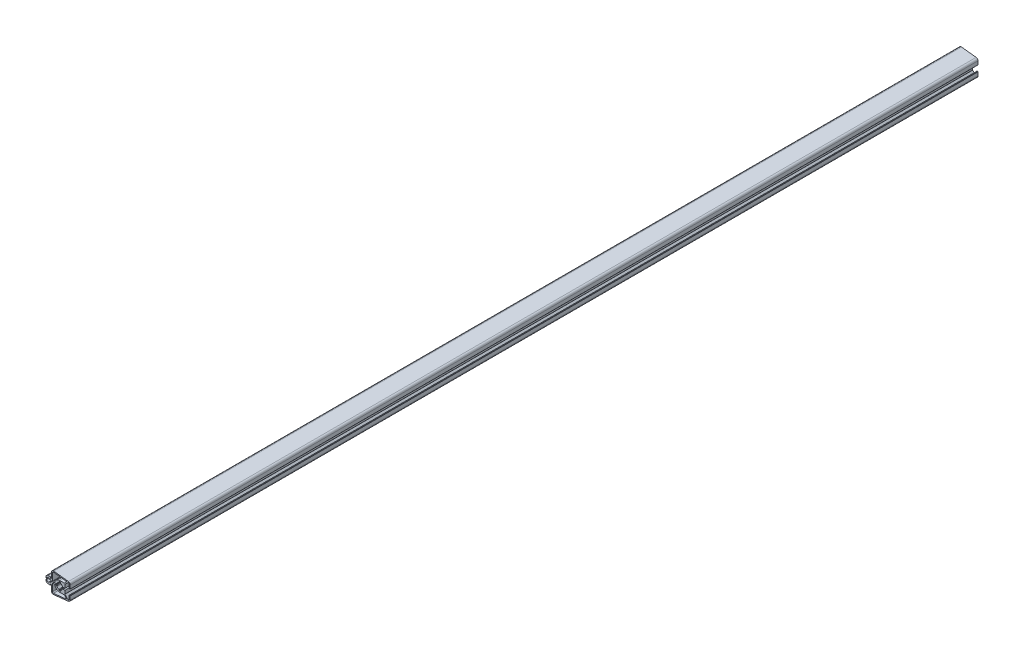
SolidWorks part; units mm, degrees
material "6061 Alloy"
ref_plane "Front Plane" through (0, 0, 0) normal (0, 0, 1) x (1, 0, 0)
ref_plane "Top Plane" through (0, 0, 0) normal (0, 1, 0) x (1, 0, 0)
ref_plane "Right Plane" through (0, 0, 0) normal (1, 0, 0) x (0, 0, -1)
sketch "Sketch1" plane through (0, 0, 0) normal (0, 0, 1) x (1, 0, 0)
  line L0 (27, 23.6023) -> (27, -23.6023) construction
  line L1 (16.5, -1.25) -> (16.5, -11.6482)
  line L2 (21.49, 1.2) -> (22.3417, 1.2)
  line L3 (13.5, 1.5) -> (12.4976, 1.5)
  line L4 (13.5, -1.5) -> (12.4976, -1.5)
  line L5 (0, 23.6023) -> (0, -23.6023) construction
  line L6 (-42, 0) -> (42, 0) construction
  line L7 (7.3, -42) -> (7.3, -0.75) construction
  line L9 (17, 0.75) -> (19.091, 0.75)
  line L10 (18.3313, 14.6299) -> (39.3313, 12.2965) construction
  line L11 (42, 4.3) -> (42, 9.3149) construction
  line L12 (40.5, 4.3) -> (40.5, 9.3149) construction
  line L13 (17, -0.75) -> (19.091, -0.75)
  line L14 (15, 11.6482) -> (15, 3.873)
  line L15 (16.5, 11.6482) -> (16.5, 1.25)
  line L16 (36.8838, -10.7323) -> (33.5101, -7.3586)
  line L17 (39.0532, -10.7804) -> (34.3586, -6.0858)
  line L18 (39.135, -10.8091) -> (39.1656, -10.8057)
  line L19 (28.2, -5.51) -> (28.2, -4.6583)
  line L20 (40.5, -4.3) -> (40.5, -9.3149)
  line L21 (42, -4.3) -> (42, -9.3149)
  line L22 (41.8, -4.1) -> (40.7, -4.1)
  line L23 (18.1656, -13.139) -> (36.7644, -11.0725)
  line L24 (18.3313, -14.6299) -> (39.3313, -12.2965)
  line L26 (16.5, -4.1) -> (10.4, 0) construction
  line L27 (7.3, -0.95) -> (7.3, -2.1377)
  line L28 (15, -11.6482) -> (15, -3.873)
  line L29 (13.5, 4.1495) -> (13.5, 5.04)
  line L30 (27, -7.3) -> (33.3686, -7.3)
  line L31 (34.3, -5.9444) -> (34.3, -1.2)
  line L32 (10.4, 5.14) -> (13.4, 5.14)
  line L33 (7.3, -4.1) -> (42, -4.1) construction
  line L34 (13.5, 4.1) -> (7.3, -4.1) construction
  line L35 (10.4, -5.14) -> (13.4, -5.14)
  line L36 (13.5, -4.1495) -> (13.5, -5.04)
  line L38 (7.3, 0) -> (7.3, 42) construction
  line L39 (7.5, 0.75) -> (7.8726, 0.75)
  line L41 (7.5, -0.75) -> (7.8726, -0.75)
  line L42 (0, 0) -> (-24.914, -24.914) construction
  line L44 (7.3, 2.1377) -> (7.3, 0.95)
  line L45 (14.0524, 0.75) -> (5.7297, 0.75) construction
  line L47 (5.7297, -0.75) -> (14.0524, -0.75) construction
  line L48 (12, 15) -> (42, 15) construction
  line L49 (-45, -45) -> (45, -45) construction
  line L50 (-45, -45) -> (-45, 45) construction
  line L51 (-45, 45) -> (45, 45) construction
  line L52 (45, -45) -> (45, 45) construction
  line L53 (-45, -45) -> (45, 45) construction
  line L54 (-45, 45) -> (45, -45) construction
  line L55 (-42, -42) -> (42, -42) construction
  line L56 (-42, -42) -> (-42, 42) construction
  line L57 (-42, 42) -> (42, 42) construction
  line L58 (42, -42) -> (42, 42) construction
  line L59 (-42, -42) -> (42, 42) construction
  line L60 (-42, 42) -> (42, -42) construction
  line L62 (41.8, 4.1) -> (40.7, 4.1)
  line L63 (42, 4.3) -> (42, 9.3149)
  line L65 (15, 0) -> (15, 42) construction
  line L66 (39.0532, 10.7804) -> (34.3586, 6.0858)
  line L67 (27, 7.3) -> (33.3686, 7.3)
  line L68 (34.3, 5.9444) -> (34.3, 1.2)
  line L69 (18.3313, 14.6299) -> (39.3313, 12.2965)
  line L72 (19.7, 7.3) -> (34.3, -7.3) construction
  line L74 (36.8838, 10.7323) -> (33.5101, 7.3586)
  line L75 (42, 4.3) -> (42, 9.813) construction
  line L76 (18.1656, 13.139) -> (36.7644, 11.0725)
  line L77 (40.5, 4.3) -> (40.5, 9.3149)
  line L78 (38.7929, 10.5201) -> (34.5929, 6.3201) construction
  line L79 (39.135, 10.8091) -> (39.1656, 10.8057)
  line L80 (7.3, 4.1) -> (42, 4.1) construction
  line L81 (40.5, 4.3) -> (40.5, 9.813) construction
  line L82 (18.1656, 13.139) -> (39.1656, 10.8057) construction
  line L83 (37.7322, 11.5808) -> (33.5322, 7.3808) construction
  line L86 (25.8, -5.51) -> (25.8, -4.6583)
  line L88 (16.5, 11.6482) -> (16.5, 0) construction
  line L89 (21.49, -1.2) -> (22.3417, -1.2)
  line L90 (15, 11.6482) -> (15, 0) construction
  line L91 (34.3, -1.2) -> (31.6583, -1.2)
  line L92 (34.3, 1.2) -> (31.6583, 1.2)
  line L93 (25.8, 5.51) -> (25.8, 4.6583)
  line L94 (28.2, 5.51) -> (28.2, 4.6583)
  arc A0 (27, 7.3) -> (19.8279, 1.3602) centre (27, 0) ccw
  arc A1 (19.8279, -1.3602) -> (27, -7.3) centre (27, 0) ccw
  arc A2 (15, 11.6482) -> (18.3313, 14.6299) centre (18, 11.6482) cw
  arc A3 (33.5101, 7.3586) -> (33.3686, 7.3) centre (33.3686, 7.5) cw
  arc A4 (34.3586, 6.0858) -> (34.3, 5.9444) centre (34.5, 5.9444) ccw
  circle A5 centre (10.4, 0) radius 5.14 construction
  arc A6 (14.1365, 3.5296) -> (13.5389, 4.0703) centre (10.4, 0) ccw
  arc A7 (42, 4.3) -> (41.8, 4.1) centre (41.8, 4.3) cw
  arc A8 (40.7, 4.1) -> (40.5, 4.3) centre (40.7, 4.3) cw
  arc A9 (15, 3.873) -> (14.1365, 3.5296) centre (14.5, 3.873) cw
  arc A10 (25.3396, -3.9665) -> (25.8, -4.6583) centre (25.05, -4.6583) cw
  arc A11 (21.2932, 1.0357) -> (21.2932, -1.0357) centre (27, 0) ccw
  arc A12 (10.4, 5.14) -> (10.1598, 5.1344) centre (10.4, 0) ccw
  arc A13 (34.3586, -6.0858) -> (34.3, -5.9444) centre (34.5, -5.9444) cw
  arc A14 (28.2, 5.51) -> (28.0357, 5.7068) centre (28, 5.51) ccw
  arc A15 (33.5101, -7.3586) -> (33.3686, -7.3) centre (33.3686, -7.5) ccw
  arc A16 (39.0532, -10.7804) -> (39.135, -10.8091) centre (39.1239, -10.7097) ccw
  arc A17 (39.1656, -10.8057) -> (40.5, -9.3149) centre (39, -9.3149) ccw
  arc A18 (39.3313, -12.2965) -> (42, -9.3149) centre (39, -9.3149) ccw
  arc A19 (40.7, -4.1) -> (40.5, -4.3) centre (40.7, -4.3) ccw
  arc A20 (42, -4.3) -> (41.8, -4.1) centre (41.8, -4.3) ccw
  arc A21 (18.1656, -13.139) -> (16.5, -11.6482) centre (18, -11.6482) cw
  arc A22 (13.4, 5.14) -> (13.5, 5.04) centre (13.4, 5.04) cw
  arc A23 (13.5, 4.1495) -> (13.5389, 4.0703) centre (13.6, 4.1495) ccw
  arc A24 (10.1598, 5.1344) -> (7.3, 2.1377) centre (10.3, 2.1377) ccw
  arc A25 (17, 0.75) -> (16.5, 1.25) centre (17, 1.25) cw
  arc A26 (15, -11.6482) -> (18.3313, -14.6299) centre (18, -11.6482) ccw
  arc A27 (36.7644, -11.0725) -> (36.8838, -10.7323) centre (36.7424, -10.8737) ccw
  circle A28 centre (10.4, 0) radius 3.1 construction
  circle A29 centre (15, 0) radius 1.5 construction
  arc A30 (17, -0.75) -> (16.5, -1.25) centre (17, -1.25) ccw
  arc A31 (10.1598, -5.1344) -> (7.3, -2.1377) centre (10.3, -2.1377) cw
  arc A32 (13.5, -4.1495) -> (13.5389, -4.0703) centre (13.6, -4.1495) cw
  arc A33 (19.091, -0.75) -> (19.8279, -1.3602) centre (19.091, -1.5) cw
  arc A34 (19.091, 0.75) -> (19.8279, 1.3602) centre (19.091, 1.5) ccw
  circle A35 centre (10.4, 0) radius 2.5 construction
  arc A36 (13.4, -5.14) -> (13.5, -5.04) centre (13.4, -5.04) ccw
  arc A37 (10.4, -5.14) -> (10.1598, -5.1344) centre (10.4, 0) cw
  arc A38 (15, -3.873) -> (14.1365, -3.5296) centre (14.5, -3.873) ccw
  arc A39 (14.1365, -3.5296) -> (13.5389, -4.0703) centre (10.4, 0) cw
  arc A40 (8.0599, 0.8796) -> (12.3422, 1.5741) centre (10.4, 0) cw
  arc A42 (8.0599, -0.8796) -> (12.3422, -1.5741) centre (10.4, 0) ccw
  arc A43 (12.3422, 1.5741) -> (12.4976, 1.5) centre (12.4976, 1.7) ccw
  arc A44 (12.4976, -1.5) -> (12.3422, -1.5741) centre (12.4976, -1.7) ccw
  arc A45 (7.3, -0.95) -> (7.5, -0.75) centre (7.5, -0.95) cw
  arc A46 (7.8726, -0.75) -> (8.0599, -0.8796) centre (7.8726, -0.95) cw
  arc A47 (8.0599, 0.8796) -> (7.8726, 0.75) centre (7.8726, 0.95) cw
  arc A48 (7.3, 0.95) -> (7.5, 0.75) centre (7.5, 0.95) ccw
  circle A49 centre (13.5, 0) radius 1.5 construction
  arc A50 (13.5, -1.5) -> (13.5, 1.5) centre (13.5, 0) ccw
  arc A61 (18.1656, 13.139) -> (16.5, 11.6482) centre (18, 11.6482) ccw
  arc A62 (39.3313, 12.2965) -> (42, 9.3149) centre (39, 9.3149) cw
  arc A63 (39.1656, 10.8057) -> (40.5, 9.3149) centre (39, 9.3149) cw
  arc A64 (39.0532, 10.7804) -> (39.135, 10.8091) centre (39.1239, 10.7097) cw
  arc A66 (37.7322, 11.5808) -> (42, 9.813) centre (39.5, 9.813) cw construction
  arc A67 (38.7929, 10.5201) -> (40.5, 9.813) centre (39.5, 9.813) cw construction
  arc A68 (36.7644, 11.0725) -> (36.8838, 10.7323) centre (36.7424, 10.8737) cw
  arc A69 (23.0335, 1.6604) -> (22.3417, 1.2) centre (22.3417, 1.95) cw
  arc A70 (28.6604, 3.9665) -> (28.2, 4.6583) centre (28.95, 4.6583) cw
  circle A71 centre (27, 0) radius 7.3 construction
  arc A73 (28.0357, -5.7068) -> (28.2, -5.51) centre (28, -5.51) ccw
  arc A74 (30.9665, -1.6604) -> (28.6604, -3.9665) centre (27, 0) cw
  arc A75 (25.3396, 3.9665) -> (23.0335, 1.6604) centre (27, 0) ccw
  arc A76 (25.9643, 5.7068) -> (25.8, 5.51) centre (26, 5.51) ccw
  arc A77 (21.2932, 1.0357) -> (21.49, 1.2) centre (21.49, 1) cw
  arc A78 (25.9643, 5.7068) -> (28.0357, 5.7068) centre (27, 0) cw
  arc A79 (30.9665, 1.6604) -> (31.6583, 1.2) centre (31.6583, 1.95) ccw
  arc A81 (28.6604, -3.9665) -> (28.2, -4.6583) centre (28.95, -4.6583) ccw
  arc A82 (23.0335, -1.6604) -> (25.3396, -3.9665) centre (27, 0) ccw
  arc A83 (28.0357, -5.7068) -> (25.9643, -5.7068) centre (27, 0) cw
  arc A84 (23.0335, -1.6604) -> (22.3417, -1.2) centre (22.3417, -1.95) ccw
  arc A85 (25.3396, 3.9665) -> (25.8, 4.6583) centre (25.05, 4.6583) ccw
  arc A86 (21.49, -1.2) -> (21.2932, -1.0357) centre (21.49, -1) cw
  arc A87 (28.6604, 3.9665) -> (30.9665, 1.6604) centre (27, 0) cw
  arc A88 (30.9665, -1.6604) -> (31.6583, -1.2) centre (31.6583, -1.95) cw
  arc A89 (25.8, -5.51) -> (25.9643, -5.7068) centre (26, -5.51) ccw
  circle A90 centre (27, 0) radius 5.8 construction
  arc A91 (18.3313, 14.6299) -> (15, 11.6482) centre (18, 11.6482) ccw construction
  point P34 (15, 2.2935)
  point P48 (15, 4.1)
  point P76 (39.0872, -10.8144)
  point P92 (14.8, -4.1)
  point P95 (15, -15)
  point P108 (14.8, 4.1)
  point P122 (7.3, -3.1)
  point P125 (7.3, 0)
  point P126 (7.3, 3.1)
  point P129 (19.7386, -0.75)
  point P132 (15, -2.2935)
  point P139 (12.4, 1.5)
  point P144 (12.4, -1.5)
  point P150 (8.0152, -0.75)
  point P153 (8.0152, 0.75)
  point P156 (7.3, 0.75)
  point P211 (-42, -0.75)
  point P212 (42, -0.75)
  point P213 (-42, 0.75)
  point P214 (42, 0.75)
  point P217 (15, 15)
  point P232 (39.0872, 10.8144)
  point P235 (13.7, 3.1)
  point P237 (47.7249, 3.1)
  point P262 (28.2, 5.6745)
  point P263 (25.8, 5.6745)
  point P288 (25.8, -5.6745)
  point P289 (28.2, -5.6745)
  dimension "D7" = 3.1
  dimension "D8" = 4.1
  dimension "D9" = 3
  dimension "D12" = 0.1
  dimension "D13" = 3
  dimension "D14" = 0.2
  dimension "D18" = 1.1
  dimension "D20" = 1.5
  dimension "D21" = 3
  dimension "D22" = 0.1
  dimension "D23" = 0.2
  dimension "D24" = 0.75
  dimension "D10" = 0.2
  dimension "D11" = 3
  dimension "D5" = 0.5
  dimension "D26" = 0.75
  dimension "D28" = 1.5
  dimension "D29" = 4.3
  dimension "D30" = 11.6
  dimension "D27" = 5
  dimension "D4" = 0.5
  dimension "D3" = 15
  dimension "D6" = 27
  dimension "D15" = 90
  dimension "D16" = 90
  dimension "D17" = 3
  dimension "D25" = 15
  dimension "D31" = 7.7
  dimension "D19" = 1.5
extrude "Extrude1" add sketch "Sketch1" along normal blind 1300
